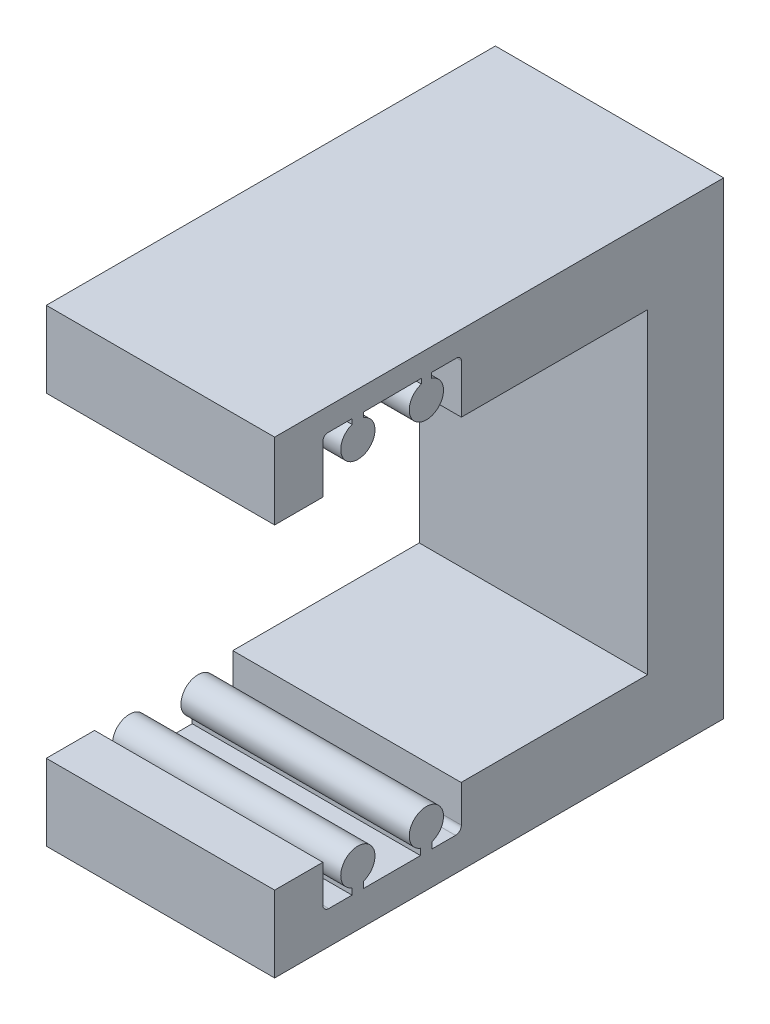
SolidWorks part; units mm, degrees
material "ABS"
ref_plane "Plano frontal" through (0, 0, 0) normal (0, 0, 1) x (1, 0, 0)
ref_plane "Plano superior" through (0, 0, 0) normal (0, 1, 0) x (1, 0, 0)
ref_plane "Plano direito" through (0, 0, 0) normal (1, 0, 0) x (0, 0, -1)
sketch "Esboço1" plane through (0, 0, 0) normal (0, 0, 1) x (1, 0, 0)
  line L0 (-15, 30.77) -> (-15, -30.77)
  line L1 (-15, -20.77) -> (15, -20.77)
  line L2 (-15, -20.77) -> (-15, 20.77)
  line L3 (-15, 20.77) -> (15, 20.77)
  line L4 (15, -20.77) -> (15, 20.77)
  line L5 (-15, -20.77) -> (15, 20.77) construction
  line L6 (-15, 20.77) -> (15, -20.77) construction
  line L7 (-15, -30.77) -> (15, -30.77)
  line L8 (15, -30.77) -> (15, 30.77)
  line L9 (15, 30.77) -> (-15, 30.77)
  point P0 (0, 0)
  point P10 (-15, 0)
  dimension "D1" = 41.54
  dimension "D2" = 30
  dimension "D3" = 10
extrude "Ressalto-extrusão1" add sketch "Esboço1" along normal blind 59 contours L8 L9 L0 L3 | L7 L8 L1 L0
sketch "Esboço2" plane through (0, 0, 0) normal (0, 0, -1) x (-1, 0, 0)
  line L0 (15, -20.77) -> (-15, -20.77) construction
  line L1 (15, 30.77) -> (15, -30.77) construction
  line L2 (15, 20.77) -> (-15, 20.77) construction
  line L3 (-15, -20.77) -> (-15, 20.77) construction
  line L4 (15, -20.77) -> (-15, -20.77)
  line L5 (15, 30.77) -> (15, -30.77)
  line L6 (15, 20.77) -> (-15, 20.77)
  line L7 (-15, -20.77) -> (-15, 20.77)
  line L8 (-15, 20.77) -> (-15, 30.77)
  line L9 (-15, 30.77) -> (15, 30.77)
  line L10 (-15, -20.77) -> (-15, -30.77)
  line L11 (-15, -30.77) -> (15, -30.77)
  line L12 (15, -20.77) -> (-15, -20.77)
  line L13 (-15, 20.77) -> (15, 20.77)
  line L14 (15, -20.77) -> (-15, -20.77)
  line M2 (-15, 20.77) -> (15, 20.77)
extrude "Ressalto-extrusão2" add sketch "Esboço2" against normal blind 10 contours L7 L4 L5 M2
sketch "Esboço3" plane through (-15, 0, 0) normal (-1, 0, 0) x (0, 0, 1)
  line L0 (31.2729, 20.77) -> (34.5, 20.77)
  line L1 (59, 20.77) -> (10, 20.77) construction
  line L2 (34.4643, 20.77) -> (34.4643, 27.1808)
  line L3 (38.4075, 27.8215) -> (38.4075, 27.1622)
  line L4 (39.7211, 27.8215) -> (39.7211, 27.1622)
  line L6 (0, 0) -> (64.8544, 0) construction
  line L7 (47.295, 27.1246) -> (47.295, 27.7839)
  line L8 (48.8337, 27.1246) -> (48.8337, 27.7839)
  line L9 (52.5643, 26.27) -> (52.5643, 20.7683) construction
  line L10 (52.5643, 20.77) -> (54.6977, 20.77)
  line L11 (34.5, 20.77) -> (52.5643, 20.77)
  line L13 (35.105, 27.8215) -> (38.1075, 27.8215)
  line L14 (38.1075, 27.8215) -> (40.0211, 27.8215)
  line L15 (40.0211, 27.8215) -> (48.8534, 27.7758)
  line L16 (48.8534, 27.7758) -> (48.8337, 27.7839)
  line L17 (48.8337, 27.7839) -> (52.0143, 27.7839)
  line L18 (52.6643, 27.1338) -> (52.6643, 20.77)
  line L19 (0, 30.77) -> (0, -30.77) construction
  line L20 (44.3337, -27.7122) -> (44.3337, -28.817) construction
  line L21 (52.6643, -25.6493) -> (52.6643, -20.77)
  line L22 (49.2154, -26.4238) -> (51.8898, -26.4238)
  line L23 (48.5337, -26.4238) -> (49.2154, -26.4238)
  line L24 (40.1337, -26.4238) -> (48.5337, -26.4238)
  line L25 (37.995, -26.4238) -> (40.1337, -26.4238)
  line L26 (35.2389, -26.4238) -> (37.995, -26.4238)
  line L27 (34.4643, -20.7704) -> (34.4643, -25.6493)
  line L28 (34.5, -20.77) -> (52.5643, -20.77)
  line L29 (52.5643, -20.77) -> (54.6977, -20.77)
  line L30 (47.295, -25.5846) -> (47.295, -26.4238)
  line L31 (48.8337, -27.7122) -> (48.8337, -25.5846)
  line L32 (39.8337, -26.4238) -> (39.8337, -25.5846)
  line L33 (38.295, -26.4238) -> (38.295, -25.5846)
  line L34 (34.4643, -20.7704) -> (34.5, -20.77)
  line L35 (31.2729, -20.77) -> (34.5, -20.77)
  line L36 (34.5643, 20.7683) -> (34.5643, 26.27) construction
  line L37 (34.5643, -19.2283) -> (34.5643, -24.73) construction
  line L38 (34.4643, -20.7704) -> (34.5, -20.77)
  line L39 (52.6643, -20.77) -> (52.5643, -20.77)
  line L40 (46.995, -25.73) -> (46.995, -26.4238) construction
  line L41 (49.1337, -25.73) -> (49.1337, -26.4238) construction
  line L42 (40.1337, -25.73) -> (40.1337, -26.4238) construction
  line L43 (37.995, -25.73) -> (37.995, -26.4238) construction
  arc A0 (38.4075, 27.1622) -> (39.7211, 27.1622) centre (39.0643, 25.0102) ccw
  arc A1 (47.295, 27.1246) -> (48.8337, 27.1246) centre (48.0643, 25.0102) ccw
  arc A2 (51.8898, -26.4238) -> (52.6643, -25.6493) centre (51.8898, -25.6493) ccw
  arc A3 (34.4643, -25.6493) -> (35.2389, -26.4238) centre (35.2389, -25.6493) ccw
  arc A4 (35.105, 27.8215) -> (34.4643, 27.1622) centre (35.1143, 27.1715) ccw
  arc A5 (52.0143, 27.7839) -> (52.6643, 27.1338) centre (52.0143, 27.1338) cw
  arc A7 (38.295, -25.5846) -> (39.8337, -25.5846) centre (39.0643, -23.4702) cw
  arc A8 (48.8337, -25.5846) -> (47.295, -25.5846) centre (48.0643, -23.4702) ccw
  point P11 (48.0643, -23.4702)
  point P19 (49.1337, 27.27)
  point P20 (46.995, 27.27)
  point P78 (39.0643, -23.4702)
  point P88 (37.995, -26.0769)
  line M13 (59, -20.77) -> (10, -20.77)
  line M15 (10, 20.77) -> (59, 20.77)
  dimension "D2" = 4.5
  dimension "D9" = 4.5
  dimension "D10" = 0.1
  dimension "D11" = 0.1
  dimension "D12" = 2.25
  dimension "D3" = 0.3
  dimension "D4" = 0.3
  dimension "D1" = 0.1
  dimension "D5" = 0.1
  dimension "D6" = 0.3
  dimension "D7" = 0.3
  dimension "D8" = 0.3
extrude "Corte-extrusão1" cut sketch "Esboço3" against normal through all contours A8 L31 L23 L22 A2 L21 L34 L27 A3 L26 L25 L33 A7 L32 L24 L30 M13 | A5 L17 L16 L15 L8 A1 L7 L14 L4 A0 L3 L13 A4 L2 L0 L18 M15
sketch "Esboço4" plane through (-15, 0, 0) normal (-1, 0, 0) x (0, 0, 1)
  line L0 (47.295, 27.7839) -> (48.8534, 27.7758)
  line L1 (48.8534, 27.7758) -> (48.8534, 27.1173)
  line L3 (47.2916, 27.1234) -> (47.295, 27.7839)
  line L4 (38.4075, 27.8215) -> (38.4075, 27.1622)
  line L6 (39.7211, 27.1622) -> (39.7211, 27.8215)
  line L7 (39.7211, 27.8215) -> (38.4075, 27.8215)
  arc A0 (38.4075, 27.1622) -> (39.7211, 27.1622) centre (39.0643, 25.0102) ccw
  arc A1 (47.2916, 27.1234) -> (48.8534, 27.1173) centre (48.0643, 25.0102) ccw
  point P19 (38.4075, 27.8937)
extrude "Corte-extrusão2" cut sketch "Esboço4" against normal blind 4
